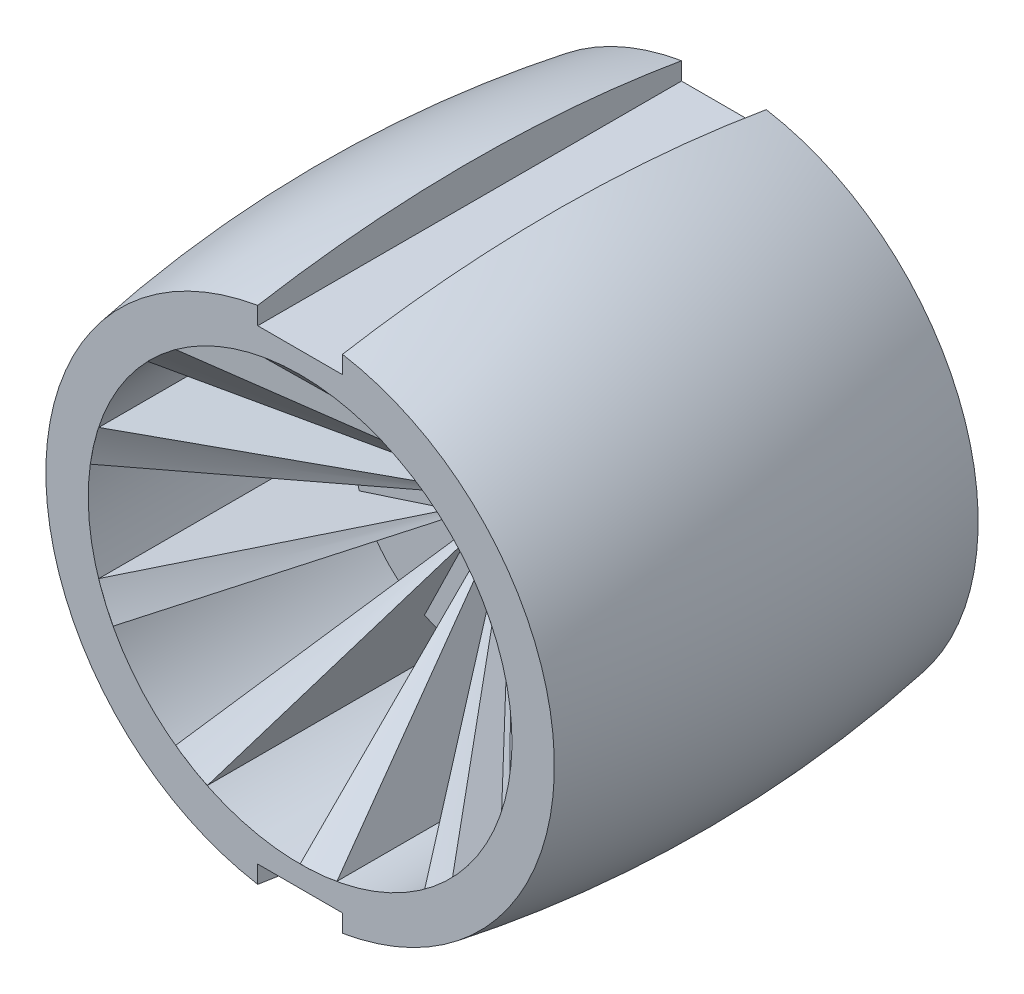
SolidWorks part; units mm, degrees
ref_plane "Front Plane" through (0, 0, 0) normal (0, 0, 1) x (1, 0, 0)
ref_plane "Top Plane" through (0, 0, 0) normal (0, 1, 0) x (1, 0, 0)
ref_plane "Right Plane" through (0, 0, 0) normal (1, 0, 0) x (0, 0, -1)
sketch "Sketch1" plane through (0, 0, 0) normal (1, 0, 0) x (0, 0, -1)
  line L0 (0, 0) -> (0, 50) construction
  line L1 (-19.054, 30) -> (21.2337, 30) construction
  line L2 (-25, 30) -> (-25, 25)
  line L3 (-25, 25) -> (25, 25)
  line L4 (25, 25) -> (25, 30)
  arc A0 (-25, 30) -> (25, 30) centre (0, -117.902) cw
  dimension "D3" = 150
  dimension "D1" = 50
  dimension "D2" = 30
  dimension "D4" = 25
  dimension "D5" = 25
  dimension "D6" = 5
sketch "Sketch2" plane through (0, 0, 0) normal (0, 0, 1) x (1, 0, 0)
  circle A0 centre (0, 0) radius 30 construction
  dimension "D1" = 60
sketch "Sketch3" plane through (0, 0, 0) normal (0, 0, 1) x (1, 0, 0)
  circle A0 centre (0, 0) radius 30
  dimension "D1" = 60
sweep "Sweep1" add profiles "Sketch1" path "Sketch3"
sketch "Sketch4" plane through (0, 0, 0) normal (0, 0, 1) x (1, 0, 0)
  circle A0 centre (0, 0) radius 3.75
  circle A1 centre (0, 0) radius 15
  dimension "D1" = 7.5
  dimension "D2" = 30
extrude "Boss-Extrude1" add sketch "Sketch4" along normal mid plane 7.5 separate body
sketch "Sketch5" plane through (0, 0, 0) normal (0, 1, 0) x (1, 0, 0)
  line L0 (0, 26.3312) -> (0, -26.1905) construction
sketch "Sketch6" plane through (0, 0, 0) normal (1, 0, 0) x (0, 0, -1)
  line L0 (-25, 25) -> (25, 25)
  line L1 (25, 25) -> (3.75, 3.75)
  line L2 (3.75, -15) -> (3.75, 15) construction
  line L4 (-3.75, 15) -> (-3.75, -15) construction
  line L5 (-3.75, 3.75) -> (-25, 25)
  line L6 (-3.75, 3.75) -> (-3.75, 15)
  line L7 (-3.75, 15) -> (3.75, 15)
  line L8 (3.75, 15) -> (3.75, 3.75)
  dimension "D1" = 45
  dimension "D2" = 45
revolve "Revolve1" add sketch "Sketch6" angle 10 about L0
pattern_circular "CirPattern1" count 10 over 360 about axis through (0, 0, 0) along (0, 0, 1) of "Revolve1"
sketch "Sketch7" plane through (0, 0, 0) normal (0, 0, 1) x (1, 0, 0)
  line L1 (-5, 35) -> (5, 35)
  line L2 (-5, 35) -> (-5, 27.5)
  line L3 (-5, 27.5) -> (5, 27.5)
  line L4 (5, 35) -> (5, 27.5)
  dimension "D1" = 27.5
  dimension "D2" = 10
  dimension "D3" = 5
  dimension "D4" = 7.5
extrude "Cut-Extrude1" cut sketch "Sketch7" against normal through all both and the other way through all
mirror "Mirror1" about plane through (0, 0, 0) normal (0, 1, 0) of "Cut-Extrude1"
